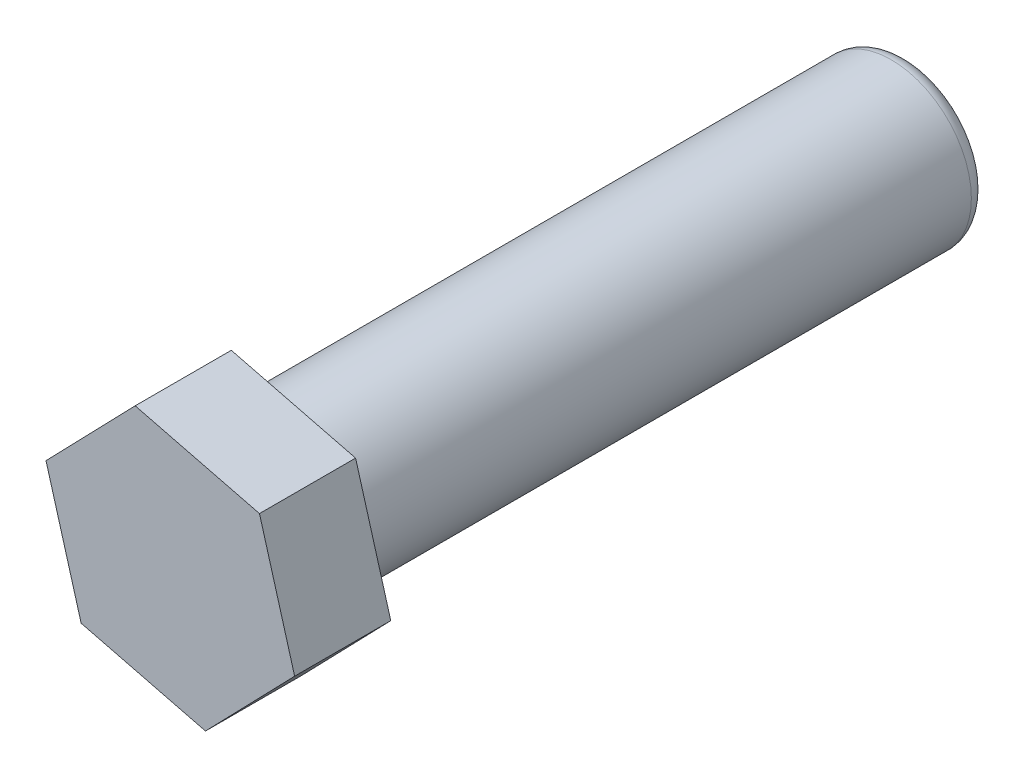
SolidWorks part; units mm, degrees
material "Alumina"
ref_plane "Front Plane" through (0, 0, 0) normal (0, 0, 1) x (1, 0, 0)
ref_plane "Top Plane" through (0, 0, 0) normal (0, 1, 0) x (1, 0, 0)
ref_plane "Right Plane" through (0, 0, 0) normal (1, 0, 0) x (0, 0, -1)
sketch "Sketch1" plane through (0, 0, 0) normal (0, 0, 1) x (1, 0, 0)
  circle A0 centre (0, 0) radius 2.5
  dimension "D1" = 5
extrude "Boss-Extrude1" add sketch "Sketch1" along normal blind 20
sketch "Sketch3" plane through (0, 0, 20) normal (0, 0, 1) x (1, 0, 0)
  line L1 (2.7824, 2.8737) -> (-1.0975, 3.8465)
  line L2 (-1.0975, 3.8465) -> (-3.8799, 0.9728)
  line L3 (-3.8799, 0.9728) -> (-2.7824, -2.8737)
  line L4 (-2.7824, -2.8737) -> (1.0975, -3.8465)
  line L5 (1.0975, -3.8465) -> (3.8799, -0.9728)
  line L6 (3.8799, -0.9728) -> (2.7824, 2.8737)
  circle A0 centre (0, 0) radius 3.4641 construction
  dimension "D1" = 8
extrude "Boss-Extrude2" add sketch "Sketch3" along normal blind 3
fillet "Fillet1" radius 0.5 1 edges at (2.5, 0, 0)
